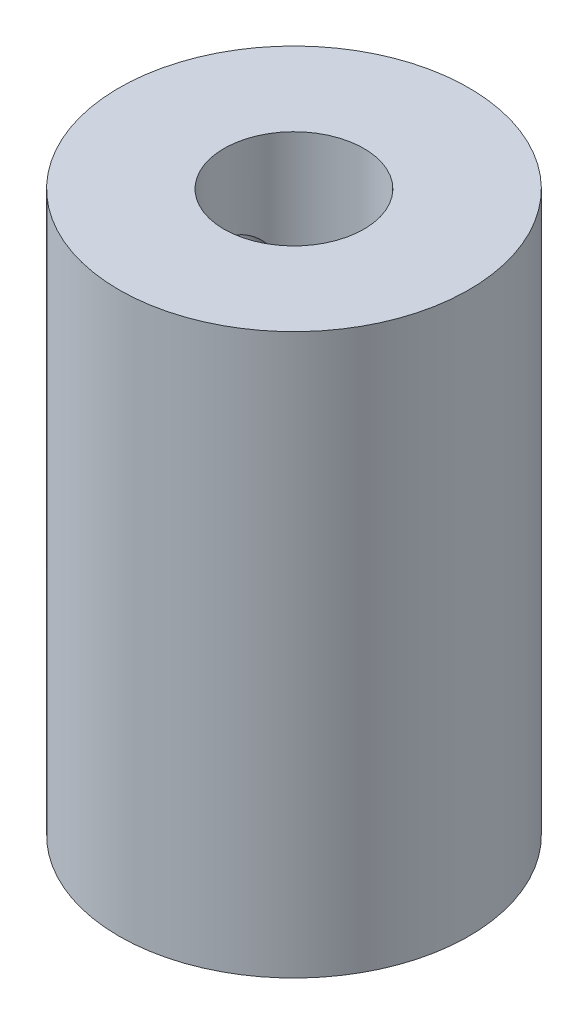
SolidWorks part; units mm, degrees
ref_plane "Front Plane" through (0, 0, 0) normal (0, 0, 1) x (1, 0, 0)
ref_plane "Top Plane" through (0, 0, 0) normal (0, 1, 0) x (1, 0, 0)
ref_plane "Right Plane" through (0, 0, 0) normal (1, 0, 0) x (0, 0, -1)
sketch "Sketch1" plane through (0, 0, 0) normal (0, 1, 0) x (1, 0, 0)
  circle A0 centre (0, 0) radius 2.1
  circle A1 centre (0, 0) radius 5
  dimension "D1" = 4.2
  dimension "D2" = 10
extrude "Boss-Extrude1" add sketch "Sketch1" along normal blind 8
sketch "Sketch2" plane through (0, 8, 0) normal (0, 1, 0) x (1, 0, 0)
  circle A0 centre (0, 0) radius 5 construction
  circle A1 centre (0, 0) radius 5
  circle A2 centre (0, 0) radius 2
  dimension "D1" = 4
extrude "Boss-Extrude2" add sketch "Sketch2" along normal blind 8
ref_plane "Plane3" through (-5, 0, 0) normal (-1, 0, 0) x (0, 0, 1)
sketch "Sketch13" plane through (-5, 0, 0) normal (-1, 0, 0) x (0, 0, 1)
  line L0 (-5, 0) -> (5, 0) construction
  line L1 (5, 16) -> (-5, 16) construction
  line L2 (-5, 0) -> (5, 0) construction
  line L3 (5, 16) -> (-5, 16) construction
  line L4 (0, 16) -> (0, 12.5) construction
  line L5 (0, 12.5) -> (0, 3.5) construction
  line L6 (0, 3.5) -> (0, 0) construction
  dimension "D1" = 3.5
hole_wizard "M3 Tapped Hole2" positions "Sketch14" profile "Sketch15" tap size "M3" standard "ISO"
sketch "Sketch14" plane through (-5, 0, 0) normal (-1, 0, 0) x (0, 0, 1)
  point P0 (0, 12.5)
  point P3 (0, 3.5)
sketch "Sketch15" plane through (-5, 12.5, 0) normal (0, 1, 0) x (0, 0, 1)
  line L0 (0, 0) -> (0, 3)
  line L1 (0, 3) -> (1.25, 3)
  line L2 (1.25, 3) -> (1.25, 0)
  line L5 (1.25, 0) -> (0, 0)
  line L11 (0, -6.35) -> (0, 107.95) construction
  dimension "Thru Tap Drill Dia." = 2.5
  dimension "Thru Tap Drill Depth" = 3
cosmetic thread "Hole Thread4" parameters "D2"=3
cosmetic thread "Hole Thread5" parameters "D2"=3
